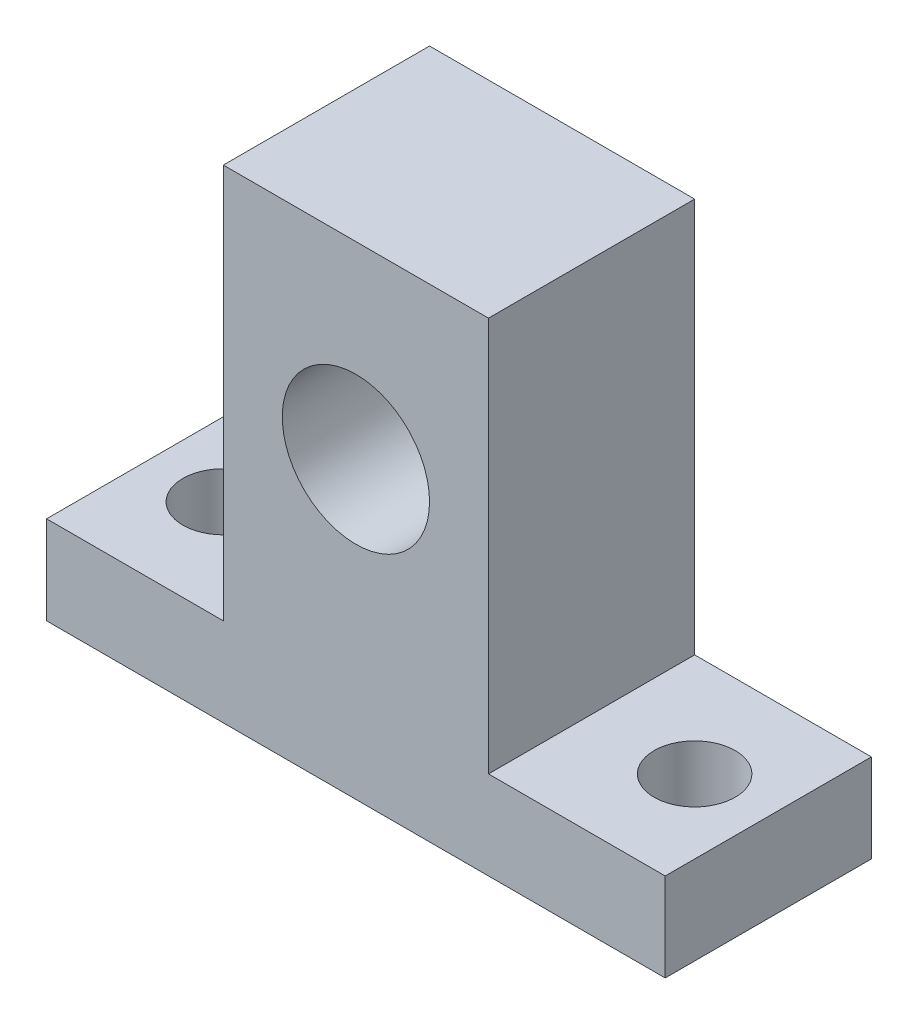
SolidWorks part; units mm, degrees
ref_plane "Front Plane" through (0, 0, 0) normal (0, 0, 1) x (1, 0, 0)
ref_plane "Top Plane" through (0, 0, 0) normal (0, 1, 0) x (1, 0, 0)
ref_plane "Right Plane" through (0, 0, 0) normal (1, 0, 0) x (0, 0, -1)
sketch "Sketch1" plane through (0, 0, 0) normal (0, 0, 1) x (1, 0, 0)
  line L0 (-21, 0) -> (21, 0)
  line L1 (21, 0) -> (21, 6)
  line L2 (21, 6) -> (9, 6)
  line L3 (9, 6) -> (9, 32.8)
  line L4 (9, 32.8) -> (-9, 32.8)
  line L5 (-9, 32.8) -> (-9, 6)
  line L6 (-9, 6) -> (-21, 6)
  line L7 (-21, 6) -> (-21, 0)
  line L8 (0, -760.0729) -> (0, 37243.5698) construction
  circle A0 centre (0, 20) radius 5
  dimension "D8" = 10
  dimension "D1" = 21
  dimension "D2" = 42
  dimension "D3" = 6
  dimension "D4" = 9
  dimension "D5" = 18
  dimension "D6" = 6
  dimension "D7" = 32.8
  dimension "D9" = 20
extrude "Boss-Extrude1" add sketch "Sketch1" along normal mid plane 14
sketch "Sketch2" plane through (0, 6, 0) normal (0, 1, 0) x (1, 0, 0)
  line L0 (-1000, 0) -> (49000, 0) construction
  circle A0 centre (-16, 0) radius 2.75
  circle A1 centre (16, 0) radius 2.75
  dimension "D1" = 5.5
  dimension "D2" = 5.5
  dimension "D3" = 32
  dimension "D4" = 16
extrude "Cut-Extrude1" cut sketch "Sketch2" against normal through all
equation "\"D6@Sketch1\"=\"D3@Sketch1\""
equation "\"D1@Sketch1\"=\"D2@Sketch1\"/2"
equation "\"D4@Sketch1\"=\"D5@Sketch1\"/2"
equation "\"D4@Sketch2\"=\"D3@Sketch2\"/2"
